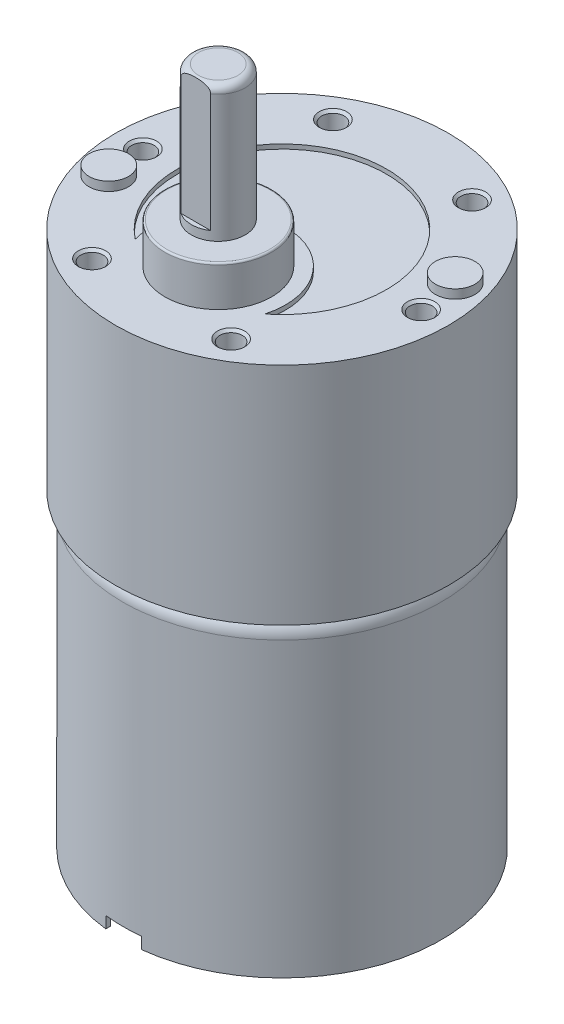
SolidWorks part; units mm, degrees
ref_plane "Front Plane" through (0, 0, 0) normal (0, 0, 1) x (1, 0, 0)
ref_plane "Top Plane" through (0, 0, 0) normal (0, 1, 0) x (1, 0, 0)
ref_plane "Right Plane" through (0, 0, 0) normal (1, 0, 0) x (0, 0, -1)
sketch "Sketch1" plane through (0, 0, 0) normal (0, 1, 0) x (1, 0, 0)
  circle A0 centre (0, 0) radius 17.75
  dimension "D1" = 35.5
extrude "Boss-Extrude1" add sketch "Sketch1" along normal blind 33.3
fillet "Fillet1" radius 2 1 edges at (0, 33.3, 17.75)
sketch "Sketch2" plane through (0, 33.3, 0) normal (0, 1, 0) x (1, 0, 0)
  circle A0 centre (0, 0) radius 18.55
  dimension "D1" = 37.1
extrude "Boss-Extrude2" add sketch "Sketch2" along normal blind 25.1
sketch "Sketch3" plane through (0, 58.4, 0) normal (0, 1, 0) x (1, 0, 0)
  line L0 (-5.4747, -13.05) -> (5.4747, -13.05) construction
  line L1 (-5.4747, -18.55) -> (5.0027, -18.55) construction
  line L2 (0, -13.05) -> (0, 0) construction
  circle A0 centre (0, -7.1) radius 5.95
  circle A1 centre (0, 0) radius 18.55 construction
  point P8 (3.2545, -7.1)
  point P9 (0, 0)
  point P13 (0, -7.1)
  dimension "D1" = 11.9
  dimension "D2" = 5.5
extrude "Boss-Extrude3" add sketch "Sketch3" along normal blind 4.5
fillet "Fillet2" radius 0.2 1 edges at (0, 62.9, 13.05)
sketch "Sketch4" plane through (0, 62.9, 0) normal (0, 1, 0) x (1, 0, 0)
  circle A0 centre (0, -7.1) radius 3
  circle A2 centre (0, -7.1) radius 5.95 construction
  point P2 (0, 0)
  point P5 (0, 0)
  point P6 (0, 0)
  dimension "D1" = 6
extrude "Boss-Extrude4" add sketch "Sketch4" along normal blind 15
fillet "Fillet3" radius 0.8 1 edges at (0, 77.9, 10.1)
sketch "Sketch6" plane through (0, 77.9, 0) normal (0, 1, 0) x (1, 0, 0)
  line L0 (-1.6583, -9.6) -> (1.6583, -9.6)
  line L1 (-2.0381, -4.1) -> (2.3027, -4.1) construction
  arc A0 (-1.6583, -9.6) -> (1.6583, -9.6) centre (0, -7.1) ccw
  circle A1 centre (0, -7.1) radius 3 construction
  circle A2 centre (0, -7.1) radius 3 construction
  dimension "D1" = 5.5
extrude "Cut-Extrude1" cut sketch "Sketch6" against normal blind 14
sketch "Sketch7" plane through (0, 58.4, 0) normal (0, 1, 0) x (1, 0, 0)
  arc A0 (7.2153, -9.1467) -> (-7.2153, -9.1467) centre (0, -7.1) ccw
  circle A1 centre (0, -7.1) radius 5.95 construction
  arc A2 (7.2153, -9.1467) -> (-7.2153, -9.1467) centre (0, 0) ccw
  dimension "D1" = 23.3
  dimension "D2" = 15
extrude "Cut-Extrude2" cut sketch "Sketch7" against normal blind 0.5
hole_wizard "M3 Tapped Hole1" positions "Sketch8" profile "Sketch10" tap size "M3" standard "ISO"
sketch "Sketch8" plane through (0, 58.4, 0) normal (0, 1, 0) x (1, 0, 0)
  line L0 (0, 0) -> (-15.5, 0) construction
  point P0 (-15.5, 0)
  dimension "D1" = 15.5
sketch "Sketch10" plane through (-15.5, 58.4, 0) normal (1, 0, 0) x (0, 0, 1)
  line L0 (0, 0) -> (0, 6.7511)
  line L1 (0, 6.7511) -> (1.25, 6)
  line L2 (1.25, 6) -> (1.25, 0.275)
  line L3 (1.25, 0.275) -> (1.525, 0)
  line L5 (1.525, 0) -> (0, 0)
  line L6 (-1.25, 0.275) -> (-1.525, 0) construction
  line L10 (0, 6.7511) -> (-1.25, 6) construction
  line L11 (0, -6.35) -> (0, 107.95) construction
  dimension "Tap Drill Dia." = 2.5
  dimension "Tap Drill Depth" = 6
  dimension "Near C'Sink Dia." = 3.05
  dimension "Near C'Sink Angle" = 90
  dimension "Drill Angle" = 118
cosmetic thread "Hole Thread1" parameters "D1"=6, "D2"=3
pattern_circular "CirPattern1" count 6 over 360 about axis through (0, 0, 0) along (0, 1, 0) of "M3 Tapped Hole1"
cosmetic thread "Hole Thread2" parameters "D1"=6, "D2"=3
cosmetic thread "Hole Thread3" parameters "D1"=6, "D2"=3
cosmetic thread "Hole Thread4" parameters "D1"=6, "D2"=3
cosmetic thread "Hole Thread5" parameters "D1"=6, "D2"=3
cosmetic thread "Hole Thread6" parameters "D1"=6, "D2"=3
sketch "Sketch11" plane through (0, 58.4, 0) normal (0, 1, 0) x (1, 0, 0)
  line L0 (-14.8468, -4.4523) -> (0, 0) construction
  circle A0 centre (-14.8468, -4.4523) radius 2.2
  circle A3 centre (-15.5, 0) radius 1.525 construction
  point P2 (-15.7797, -1.4991)
  point P5 (0, 0)
  point P9 (0, 0)
  dimension "D2" = 4.4
  dimension "D3" = 4.5
  dimension "D1" = 15.5
extrude "Boss-Extrude5" add sketch "Sketch11" along normal blind 1
pattern_circular "CirPattern2" count 2 over 360 about axis through (0, 0, 0) along (0, 1, 0) of "Boss-Extrude5"
sketch "Sketch12" plane through (0, 0, 0) normal (0, -1, 0) x (1, 0, 0)
  line L0 (-2, 17.1337) -> (-2, 17.637)
  line L1 (2, 17.1337) -> (2, 17.637)
  line L2 (0, 0) -> (0, 17.75) construction
  line L3 (-2, 16.412) -> (2, 16.412) construction
  arc A0 (-2, 17.637) -> (2, 17.637) centre (0, 0) ccw
  circle A1 centre (0, 0) radius 17.75 construction
  arc A2 (-2, 17.1337) -> (2, 17.1337) centre (0, 0) ccw
  point P10 (0, 16.412)
  point P13 (0, 0)
  point P14 (0, 0)
  point P15 (0, 0)
  dimension "D2" = 17.75
  dimension "D3" = 17.25
  dimension "D1" = 4
extrude "Boss-Extrude6" add sketch "Sketch12" along normal blind 1.3
sketch "Sketch14" plane through (0, 0, 0) normal (0, 0, 1) x (1, 0, 0)
  line L0 (0, -3.8) -> (0.9, -3.8)
  line L1 (0.9, -3.8) -> (0.9, -3.3)
  line L2 (0.9, -3.3) -> (1.75, -3.3)
  line L3 (1.75, -3.3) -> (1.75, -4.5)
  line L4 (1.75, -4.5) -> (2.55, -4.5)
  line L5 (2.55, -4.5) -> (3.55, -2.9)
  line L6 (3.55, -2.9) -> (4.55, -2.9)
  line L7 (4.55, -2.9) -> (5.05, 0)
  line L8 (5.05, 0) -> (0, 0)
  line L9 (0, 0) -> (0, -3.8)
  line L10 (-2, 0) -> (2, 0) construction
  point P12 (2.1797, -1.8934)
  point P13 (0, 0)
  point P15 (4.4984, -2.9)
  point P16 (4.55, -2.9)
  point P17 (2.7529, -3.7142)
  point P18 (2.2246, -4.5)
  dimension "D1" = 0.9
  dimension "D2" = 1.75
  dimension "D3" = 5.05
  dimension "D4" = 3.55
  dimension "D5" = 2.9
  dimension "D6" = 1
  dimension "D7" = 4.5
  dimension "D8" = 0.8
  dimension "D9" = 0.7
  dimension "D10" = 0.5
revolve "Revolve1" add sketch "Sketch14" angle 360 about L9
fillet "Fillet4" radius 0.2 2 edges at (-4.55, -2.9, 0) (0, 0, 5.05)
sketch "Sketch15" plane through (0, 0, 0) normal (0, -1, 0) x (1, 0, 0)
  line L0 (-1.2, 11) -> (1.2, 11) construction
  line L1 (-1.2, 12.75) -> (1.2, 12.75)
  line L2 (-1.2, 9.25) -> (1.2, 9.25)
  line L3 (0, 0) -> (0, 11) construction
  line L4 (-2.95, 15.3513) -> (-2.95, 10.2405) construction
  line L5 (2.95, 15.3513) -> (2.95, 10.2405) construction
  arc A0 (-1.2, 12.75) -> (-1.2, 9.25) centre (-1.2, 11) ccw
  arc A1 (1.2, 9.25) -> (1.2, 12.75) centre (1.2, 11) ccw
  point P2 (0, 11)
  point P12 (1.2, 12.7241)
  dimension "D1" = 3.5
  dimension "D2" = 5.9
  dimension "D3" = 12.75
extrude "Boss-Extrude7" add sketch "Sketch15" along normal blind 1
ref_plane "Plane1" through (0, 0, 11) normal (0, 0, -1) x (-1, 0, 0)
sketch "Sketch16" plane through (0, 0, 11) normal (0, 0, -1) x (-1, 0, 0)
  line L0 (0, -2.75) -> (0, -4.55) construction
  line L1 (-1.45, -1) -> (1.45, -1)
  line L2 (-1.45, -1) -> (-1.45, -4.55)
  line L4 (1.45, -1) -> (1.45, -4.55)
  line L5 (0.75, -2.75) -> (0.75, -4.55)
  line L6 (-0.75, -2.75) -> (-0.75, -4.55)
  line L7 (-0.5851, -6) -> (1.7889, -6) construction
  line L8 (1.2, -1) -> (2.95, -1) construction
  line L9 (-0.5851, -2) -> (1.4813, -2) construction
  line L10 (-2.075, -1) -> (2.075, -1) construction
  line L11 (1.2, -1) -> (2.95, -1) construction
  line L12 (-2.95, -1) -> (-1.2, -1) construction
  arc A0 (-1.45, -4.55) -> (1.45, -4.55) centre (0, -4.55) ccw
  arc A1 (0.75, -2.75) -> (-0.75, -2.75) centre (0, -2.75) ccw
  arc A2 (-0.75, -4.55) -> (0.75, -4.55) centre (0, -4.55) ccw
  point P6 (0, -3.65)
  point P18 (0, 0)
  point P26 (0, -1)
  dimension "D1" = 2.9
  dimension "D2" = 5
  dimension "D3" = 1.5
  dimension "D4" = 1
extrude "Boss-Extrude8" add sketch "Sketch16" along normal mid plane 0.6
pattern_circular "CirPattern3" count 2 over 360 about axis through (0, 0, 0) along (0, 1, 0) of "Boss-Extrude8", "Boss-Extrude7"
